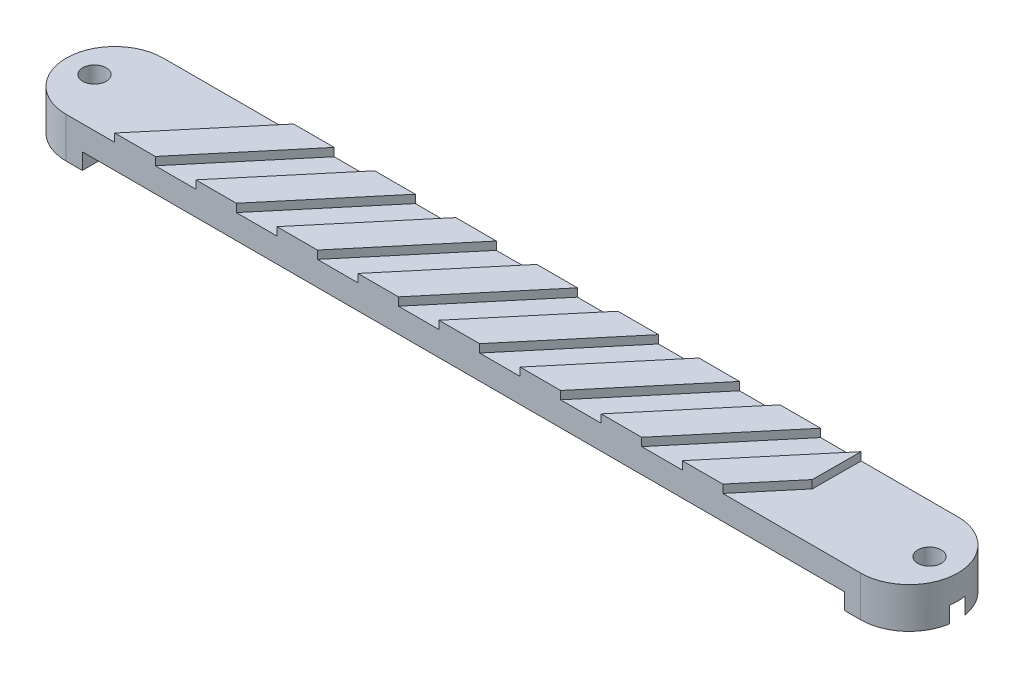
SolidWorks part; units mm, degrees
ref_plane "Front Plane" through (0, 0, 0) normal (0, 0, 1) x (1, 0, 0)
ref_plane "Top Plane" through (0, 0, 0) normal (0, 1, 0) x (1, 0, 0)
ref_plane "Right Plane" through (0, 0, 0) normal (1, 0, 0) x (0, 0, -1)
sketch "Sketch1" plane through (0, 0, 0) normal (0, 1, 0) x (1, 0, 0)
  line L0 (-49, 0) -> (49, 0) construction
  line L1 (-49, 6) -> (49, 6)
  line L2 (-49, -6) -> (49, -6)
  arc A0 (-49, 6) -> (-49, -6) centre (-49, 0) ccw
  arc A1 (49, -6) -> (49, 6) centre (49, 0) ccw
  circle A2 centre (-51.5, 0) radius 1.45
  circle A3 centre (51.5, 0) radius 1.45
  point P2 (0, 0)
  point P12 (-55, 0)
  point P13 (55, 0)
  dimension "D3" = 2.9
  dimension "D4" = 3.5
  dimension "D1" = 110
  dimension "D2" = 12
  dimension "D5" = 3.5
extrude "Boss-Extrude1" add sketch "Sketch1" along normal blind 3 contours L2 A1 L1 A0 | A2 | A3
sketch "Sketch2" plane through (0, 0, 0) normal (0, -1, 0) x (1, 0, 0)
  line L0 (-49, 6) -> (49, 6) construction
  line L1 (53.4919, -3.45) -> (55.4837, 0)
  line L2 (55.4837, 0) -> (53.4919, 3.45)
  line L3 (53.4919, 3.45) -> (49.5081, 3.45)
  line L4 (49.5081, 3.45) -> (47.5163, 0)
  line L5 (47.5163, 0) -> (49.5081, -3.45)
  line L6 (49.5081, -3.45) -> (53.4919, -3.45)
  line L7 (47, 6) -> (47, -6)
  line L8 (-49, -6) -> (49, -6) construction
  line L9 (47, -6) -> (49, -6)
  line L10 (49, 6) -> (47, 6)
  line L11 (0, 0) -> (0, -50000) construction
  line L12 (-49, 6) -> (-47, 6)
  line L13 (-47, -6) -> (-49, -6)
  line L14 (-47, 6) -> (-47, -6)
  line L15 (-49.5081, -3.45) -> (-53.4919, -3.45)
  line L16 (-47.5163, 0) -> (-49.5081, -3.45)
  line L17 (-49.5081, 3.45) -> (-47.5163, 0)
  line L18 (-53.4919, 3.45) -> (-49.5081, 3.45)
  line L19 (-55.4837, 0) -> (-53.4919, 3.45)
  line L20 (-53.4919, -3.45) -> (-55.4837, 0)
  circle A5 centre (51.5, 0) radius 1.45 construction
  circle A6 centre (51.5, 0) radius 1.45
  circle A7 centre (51.5, 0) radius 3.45 construction
  arc A8 (49, -6) -> (49, 6) centre (49, 0) ccw
  circle A9 centre (-51.5, 0) radius 3.45 construction
  arc A10 (-49, -6) -> (-49, 6) centre (-49, 0) cw
  circle A11 centre (-51.5, 0) radius 1.45
  arc M4 (-49, 6) -> (-49, -6) centre (-49, 0) ccw
  line M5 (-49, -6) -> (49, -6)
  arc M6 (49, -6) -> (49, 6) centre (49, 0) ccw
  line M7 (49, 6) -> (-49, 6)
  dimension "D1" = 6.9
  dimension "D3" = 2
extrude "Boss-Extrude2" add sketch "Sketch2" along normal blind 2 contours L7 L6 L5 L4 L3 L2 L1 M7 M5 M6 | L14 L15 L20 L19 L18 L17 L16 M7 M4 M5
sketch "Sketch3" plane through (0, 3, 0) normal (0, 1, 0) x (1, 0, 0)
  line L0 (-32.9308, 6) -> (-43, -6)
  line L1 (-49, 6) -> (49, 6) construction
  line L2 (-49, -6) -> (49, -6) construction
  line L3 (-43, -6) -> (-38, -6)
  line L4 (-38, -6) -> (-27.9308, 6)
  line L5 (-27.9308, 6) -> (-32.9308, 6)
  line L6 (-17.9308, 6) -> (-22.9308, 6)
  line L7 (-22.9308, 6) -> (-33, -6)
  line L8 (-33, -6) -> (-28, -6)
  line L9 (-28, -6) -> (-17.9308, 6)
  line L10 (-7.9308, 6) -> (-12.9308, 6)
  line L11 (-12.9308, 6) -> (-23, -6)
  line L12 (-23, -6) -> (-18, -6)
  line L13 (-18, -6) -> (-7.9308, 6)
  line L14 (2.0692, 6) -> (-2.9308, 6)
  line L15 (-2.9308, 6) -> (-13, -6)
  line L16 (-13, -6) -> (-8, -6)
  line L17 (-8, -6) -> (2.0692, 6)
  line L18 (12.0692, 6) -> (7.0692, 6)
  line L19 (7.0692, 6) -> (-3, -6)
  line L20 (-3, -6) -> (2, -6)
  line L21 (2, -6) -> (12.0692, 6)
  line L22 (22.0692, 6) -> (17.0692, 6)
  line L23 (17.0692, 6) -> (7, -6)
  line L24 (7, -6) -> (12, -6)
  line L25 (12, -6) -> (22.0692, 6)
  line L26 (32.0692, 6) -> (27.0692, 6)
  line L27 (27.0692, 6) -> (17, -6)
  line L28 (17, -6) -> (22, -6)
  line L29 (22, -6) -> (32.0692, 6)
  line L31 (37.0692, 6) -> (27, -6)
  line L32 (27, -6) -> (32, -6)
  line L33 (32, -6) -> (37.0346, 0)
  line L34 (37.0692, 6) -> (37.0346, 0)
  line L36 (42.0692, 6) -> (37.0692, 6) [skipped]
  arc A0 (-49, 6) -> (-49, -6) centre (-49, 0) ccw construction
  point P39 (-55, 0)
  dimension "D1" = 5
  dimension "D2" = 50
  dimension "D4" = 12
  dimension "D3" = 8
extrude "Boss-Extrude3" add sketch "Sketch3" along normal blind 1
